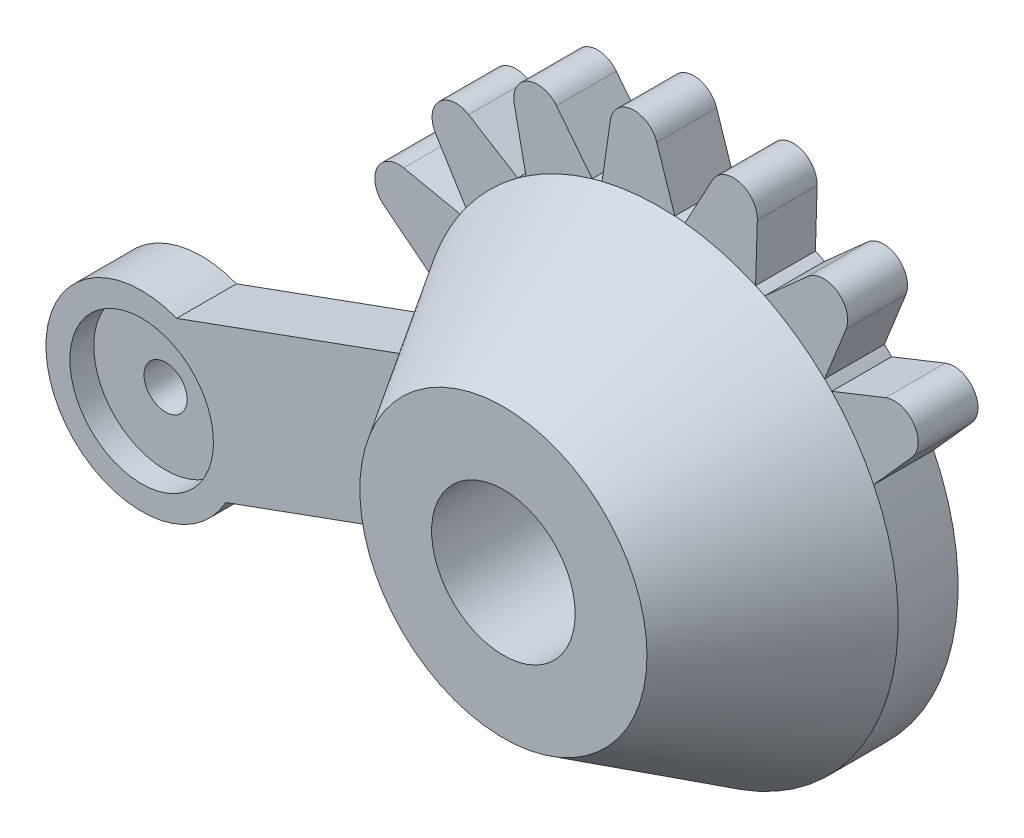
SolidWorks part; units mm, degrees
ref_plane "Alzado" through (0, 0, 0) normal (0, 0, 1) x (1, 0, 0)
ref_plane "Planta" through (0, 0, 0) normal (0, 1, 0) x (1, 0, 0)
ref_plane "Vista lateral" through (0, 0, 0) normal (1, 0, 0) x (0, 0, -1)
sketch "Croquis1" plane through (0, 0, 0) normal (0, 0, 1) x (1, 0, 0)
  circle A0 centre (-153.0518, -38.5646) radius 10
extrude "Saliente-Extruir1" add sketch "Croquis1" along normal blind 9
chamfer "Chaflán1" distance 6.5 distance2 4 1 edges at (-143.0518, -38.5646, 9)
sketch "Croquis3" plane through (0, 0, 0) normal (0, 0, -1) x (-1, 0, 0)
  line L0 (153.0518, -38.5646) -> (174.6689, -46.4197) construction
  line L1 (152.0272, -41.3842) -> (171.1576, -48.3357)
  line L2 (154.0764, -35.745) -> (173.2068, -42.6965)
  line L3 (152.0272, -41.3842) -> (173.6443, -49.2393) construction
  line L4 (154.0764, -35.745) -> (175.6934, -43.6) construction
  line L5 (154.0764, -35.745) -> (152.0272, -41.3842)
  arc A0 (171.1576, -48.3357) -> (173.2068, -42.6965) centre (174.6689, -46.4197) ccw
  dimension "D1" = 23
  dimension "D2" = 3
  dimension "D3" = 3
extrude "Saliente-Extruir3" add sketch "Croquis3" against normal blind 2.5
sketch "Croquis4" plane through (0, 0, 9) normal (0, 0, 1) x (1, 0, 0)
  circle A0 centre (-153.0518, -38.5646) radius 3
  dimension "D1" = 6
extrude "Cortar-Extruir1" cut sketch "Croquis4" against normal through all
sketch "Croquis5" plane through (0, 0, 2.5) normal (0, 0, 1) x (1, 0, 0)
  circle A0 centre (-174.6689, -46.4197) radius 3
extrude "Cortar-Extruir2" cut sketch "Croquis5" against normal blind 1
sketch "Croquis6" plane through (0, 0, 1.5) normal (0, 0, 1) x (1, 0, 0)
  circle A0 centre (-174.6689, -46.4197) radius 0.9015
extrude "Cortar-Extruir3" cut sketch "Croquis6" against normal blind 16
sketch "Croquis7" plane through (0, 0, 0) normal (0, 0, -1) x (-1, 0, 0)
  line L0 (153.0518, -38.5646) -> (174.6689, -46.4197) construction
  line L1 (153.0518, -38.5646) -> (164.8309, -33.0643) construction
  line L2 (165.2936, -34.0552) -> (164.3682, -32.0735) construction
  line L3 (161.478, -32.9745) -> (162.7473, -35.6928) construction
  line L4 (162.6527, -35.7676) -> (164.5449, -34.272)
  line L5 (161.3599, -32.999) -> (163.7214, -32.5084)
  line L6 (158.9553, -30.4932) -> (161.0066, -29.2244)
  line L7 (161.117, -32.6526) -> (162.3836, -30.6)
  line L8 (155.8387, -28.9608) -> (157.3323, -27.067)
  line L9 (158.6086, -30.2506) -> (159.0968, -27.8886)
  line L10 (152.3859, -28.5868) -> (153.1417, -26.2964)
  line L11 (155.4299, -28.8515) -> (155.0808, -26.465)
  line L12 (149.0135, -29.4163) -> (148.9403, -27.0055)
  line L13 (151.9644, -28.6239) -> (150.8202, -26.5007)
  line L14 (146.1281, -31.3492) -> (145.2348, -29.1088)
  line L15 (148.6301, -29.5953) -> (146.8286, -27.9915)
  line L16 (144.0778, -34.1523) -> (142.4722, -32.3526)
  line L17 (145.8291, -31.6485) -> (143.5877, -30.7576)
  arc A0 (163.0422, -39.0029) -> (160.993, -44.6422) centre (153.0518, -38.5646) ccw construction
  arc A1 (163.0422, -39.0029) -> (160.993, -44.6422) centre (153.0518, -38.5646) ccw
  arc A2 (164.5449, -34.272) -> (163.7214, -32.5084) centre (163.9248, -33.4874) ccw
  arc A3 (162.5896, -35.5596) -> (162.5928, -41.5596) centre (153.0518, -38.5646) ccw
  arc A4 (162.3836, -30.6) -> (161.0066, -29.2244) centre (161.5326, -30.0748) ccw
  arc A5 (160.9866, -32.4787) -> (163.0417, -38.1157) centre (153.0518, -38.5646) ccw
  arc A6 (159.0968, -27.8886) -> (157.3323, -27.067) centre (158.1175, -27.6862) ccw
  arc A7 (158.4266, -30.1318) -> (162.2857, -34.7261) centre (153.0518, -38.5646) ccw
  arc A8 (155.0808, -26.465) -> (153.1417, -26.2964) centre (154.0914, -26.6097) ccw
  arc A9 (155.2183, -28.8021) -> (160.416, -31.7994) centre (153.0518, -38.5646) ccw
  arc A10 (150.8202, -26.5007) -> (148.9403, -27.0055) centre (149.9399, -26.9751) ccw
  arc A11 (151.7486, -28.6499) -> (157.658, -29.6886) centre (153.0518, -38.5646) ccw
  arc A12 (146.8286, -27.9915) -> (145.2348, -29.1088) centre (146.1637, -28.7384) ccw
  arc A13 (148.4362, -29.6935) -> (154.3445, -28.6485) centre (153.0518, -38.5646) ccw
  arc A14 (143.5877, -30.7576) -> (142.4722, -32.3526) centre (143.2183, -31.6869) ccw
  point P11 (162.1126, -34.3336)
  point P62 (153.0518, -38.5646)
  arc M3 (163.0422, -39.0029) -> (160.993, -44.6422) centre (153.0518, -38.5646) ccw
  dimension "D5" = 2
  dimension "D1" = 45
  dimension "D2" = 13
  dimension "D3" = 2.1872
  dimension "D4" = 3
  dimension "D6" = 7
extrude "Saliente-Extruir4" add sketch "Croquis7" against normal blind 2.5 contours L17 A14 L16 M3 | L15 A12 L14 A11 M3 | L13 A10 L12 A9 M3 | L11 A8 L10 A9 A7 M3 | L9 A6 L8 A7 A5 M3 | L7 A4 L6 A5 A3 M3 | L4 A2 L5 A3 A1 M3
